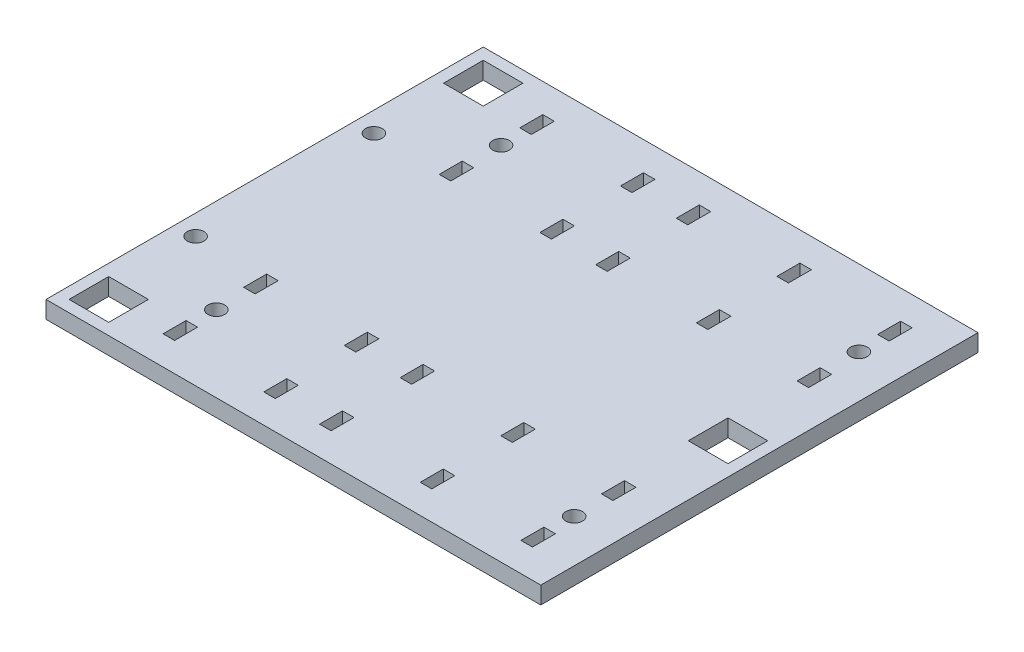
SolidWorks part; units mm, degrees
material "Chêne"
ref_plane "Plan de face" through (0, 0, 0) normal (0, 0, 1) x (1, 0, 0)
ref_plane "Plan de dessus" through (0, 0, 0) normal (0, 1, 0) x (1, 0, 0)
ref_plane "Plan de droite" through (0, 0, 0) normal (1, 0, 0) x (0, 0, -1)
sketch "Esquisse1" plane through (0, 0, 0) normal (0, 1, 0) x (1, 0, 0)
  line L1 (0, 0) -> (86, 0)
  line L4 (86, 0) -> (86, 76)
  line L5 (-1003.8634, 38) -> (102.4592, 38) construction
  line L6 (60.05, 9) -> (62.05, 9)
  line L7 (15.35, 9) -> (17.35, 9)
  line L8 (15.35, 9) -> (15.35, 5)
  line L9 (15.35, 5) -> (17.35, 5)
  line L10 (17.35, 9) -> (17.35, 5)
  line L11 (77.1, 41.45) -> (77.1, 34.55)
  line L12 (77.1, 34.55) -> (84, 34.55)
  line L13 (84, 41.45) -> (84, 34.55)
  line L14 (32.85, 9) -> (34.85, 9)
  line L15 (60.05, 9) -> (60.05, 5)
  line L16 (60.05, 5) -> (62.05, 5)
  line L17 (62.05, 9) -> (62.05, 5)
  line L18 (2, 2) -> (8.9, 2)
  line L19 (2, 2) -> (2, 8.9)
  line L20 (2, 8.9) -> (8.9, 8.9)
  line L21 (8.9, 2) -> (8.9, 8.9)
  line L22 (32.85, 9) -> (32.85, 5)
  line L23 (32.85, 5) -> (34.85, 5)
  line L24 (34.85, 9) -> (34.85, 5)
  line L25 (32.85, 23) -> (34.85, 23)
  line L26 (32.85, 23) -> (32.85, 19)
  line L30 (32.85, 19) -> (34.85, 19)
  line L31 (34.85, 23) -> (34.85, 19)
  line L32 (15.35, 23) -> (17.35, 23)
  line L33 (15.35, 23) -> (15.35, 19)
  line L34 (15.35, 19) -> (17.35, 19)
  line L35 (17.35, 23) -> (17.35, 19)
  line L36 (77.55, 9) -> (79.55, 9)
  line L37 (77.55, 9) -> (77.55, 5)
  line L38 (77.55, 5) -> (79.55, 5)
  line L39 (79.55, 9) -> (79.55, 5)
  line L40 (77.55, 23) -> (79.55, 23)
  line L41 (77.55, 23) -> (77.55, 19)
  line L45 (77.55, 19) -> (79.55, 19)
  line L46 (79.55, 23) -> (79.55, 19)
  line L47 (60.05, 23) -> (62.05, 23)
  line L48 (60.05, 23) -> (60.05, 19)
  line L49 (60.05, 19) -> (62.05, 19)
  line L50 (62.05, 23) -> (62.05, 19)
  line L51 (102.4592, 38) -> (50004.5782, 38) construction
  line L54 (62.05, 53) -> (62.05, 57)
  line L56 (60.05, 57) -> (62.05, 57)
  line L57 (60.05, 53) -> (60.05, 57)
  line L58 (60.05, 53) -> (62.05, 53)
  line L59 (79.55, 53) -> (79.55, 57)
  line L60 (77.55, 57) -> (79.55, 57)
  line L64 (77.55, 53) -> (77.55, 57)
  line L65 (77.55, 53) -> (79.55, 53)
  line L66 (79.55, 67) -> (79.55, 71)
  line L67 (77.55, 71) -> (79.55, 71)
  line L68 (77.55, 67) -> (77.55, 71)
  line L69 (77.55, 67) -> (79.55, 67)
  line L70 (17.35, 53) -> (17.35, 57)
  line L71 (15.35, 57) -> (17.35, 57)
  line L72 (15.35, 53) -> (15.35, 57)
  line L73 (15.35, 53) -> (17.35, 53)
  line L74 (34.85, 53) -> (34.85, 57)
  line L75 (32.85, 57) -> (34.85, 57)
  line L79 (32.85, 53) -> (32.85, 57)
  line L80 (32.85, 53) -> (34.85, 53)
  line L81 (34.85, 67) -> (34.85, 71)
  line L82 (32.85, 71) -> (34.85, 71)
  line L83 (32.85, 67) -> (32.85, 71)
  line L84 (8.9, 74) -> (8.9, 67.1)
  line L85 (2, 67.1) -> (8.9, 67.1)
  line L86 (2, 74) -> (2, 67.1)
  line L87 (2, 74) -> (8.9, 74)
  line L88 (62.05, 67) -> (62.05, 71)
  line L89 (60.05, 71) -> (62.05, 71)
  line L90 (60.05, 67) -> (60.05, 71)
  line L91 (32.85, 67) -> (34.85, 67)
  line L92 (77.1, 41.45) -> (84, 41.45)
  line L93 (17.35, 67) -> (17.35, 71)
  line L94 (15.35, 71) -> (17.35, 71)
  line L95 (15.35, 67) -> (15.35, 71)
  line L96 (15.35, 67) -> (17.35, 67)
  line L97 (60.05, 67) -> (62.05, 67)
  line L99 (0, 76) -> (0, 0)
  line L100 (0, 76) -> (86, 76)
  line L110 (44.55, 53) -> (44.55, 57)
  line L111 (42.55, 9) -> (44.55, 9)
  line L112 (42.55, 9) -> (42.55, 5)
  line L113 (42.55, 5) -> (44.55, 5)
  line L114 (44.55, 9) -> (44.55, 5)
  line L115 (42.55, 23) -> (44.55, 23)
  line L116 (42.55, 23) -> (42.55, 19)
  line L117 (42.55, 19) -> (44.55, 19)
  line L118 (44.55, 23) -> (44.55, 19)
  line L119 (42.55, 57) -> (44.55, 57)
  line L120 (42.55, 53) -> (42.55, 57)
  line L121 (42.55, 53) -> (44.55, 53)
  line L122 (44.55, 67) -> (44.55, 71)
  line L123 (42.55, 71) -> (44.55, 71)
  line L124 (42.55, 67) -> (42.55, 71)
  line L125 (42.55, 67) -> (44.55, 67)
  circle A0 centre (16.35, 13.25) radius 1.45
  circle A1 centre (78.55, 13.25) radius 1.45
  circle A2 centre (78.55, 62.75) radius 1.45
  circle A3 centre (16.35, 62.75) radius 1.45
  circle A4 centre (3.5, 22.5) radius 1.45
  circle A5 centre (3.5, 53.5) radius 1.45
  point P110 (84, 38)
  point P111 (77.1, 38)
  point P116 (86, 38)
  point P123 (78.55, 9)
  point P124 (16.35, 9)
  dimension "D2" = 38
  dimension "D24" = 2.9
  dimension "D25" = 2.9
  dimension "D29" = 7.45
  dimension "D20" = 2.9
  dimension "D3" = 86
  dimension "D4" = 15.5
  dimension "D5" = 2
  dimension "D6" = 6.9
  dimension "D7" = 15.5
  dimension "D8" = 15.5
  dimension "D9" = 62.2
  dimension "D10" = 2
  dimension "D11" = 4
  dimension "D12" = 5
  dimension "D13" = 10
  dimension "D14" = 2
  dimension "D15" = 2
  dimension "D16" = 3.5
  dimension "D17" = 10
  dimension "D18" = 2
  dimension "D19" = 15.5
  dimension "D26" = 3.45
  dimension "D27" = 24.75
  dimension "D30" = 2
extrude "Boss.-Extru.1" add sketch "Esquisse1" along normal blind 3
